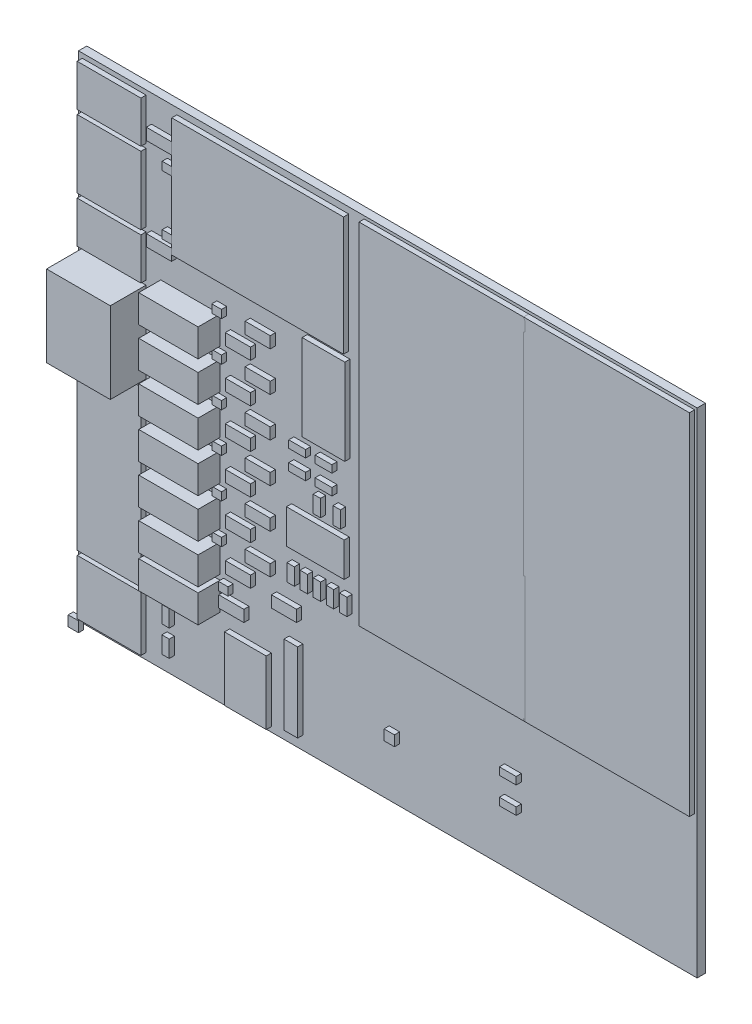
SolidWorks part; units mm, degrees
ref_plane "Front Plane" through (0, 0, 0) normal (0, 0, 1) x (1, 0, 0)
ref_plane "Top Plane" through (0, 0, 0) normal (0, 1, 0) x (1, 0, 0)
ref_plane "Right Plane" through (0, 0, 0) normal (1, 0, 0) x (0, 0, -1)
sketch "Sketch1" plane through (0, 0, 0) normal (0, 0, 1) x (1, 0, 0)
  line L0 (0, 0) -> (119.36, 0)
  line L1 (119.36, 0) -> (119.36, 95.25)
  line L2 (119.36, 95.25) -> (0, 95.25)
  line L3 (0, 95.25) -> (0, 0)
extrude "BOARD" add sketch "Sketch1" along normal blind 1.6 separate body
ref_plane "Plane1" through (0, 0, 1.6) normal (0, 0, 1) x (1, 0, 0)
sketch "Sketch2" plane through (0, 0, 1.6) normal (0, 0, 1) x (1, 0, 0)
  line L0 (42.6354, 30.8354) -> (42.6354, 27.5846)
  line L1 (42.6354, 27.5846) -> (41.21, 27.5846)
  line L2 (41.21, 27.5846) -> (41.21, 30.8354)
  line L3 (41.21, 30.8354) -> (42.6354, 30.8354)
extrude "0603-1" add sketch "Sketch2" along normal blind 1 separate body
sketch "Sketch3" plane through (0, 0, 1.6) normal (0, 0, 1) x (1, 0, 0)
  line L0 (47.7154, 30.8354) -> (47.7154, 27.5846)
  line L1 (47.7154, 27.5846) -> (46.29, 27.5846)
  line L2 (46.29, 27.5846) -> (46.29, 30.8354)
  line L3 (46.29, 30.8354) -> (47.7154, 30.8354)
extrude "0603-2" add sketch "Sketch3" along normal blind 1 separate body
sketch "Sketch4" plane through (0, 0, 1.6) normal (0, 0, 1) x (1, 0, 0)
  line L0 (45.1754, 30.8354) -> (45.1754, 27.5846)
  line L1 (45.1754, 27.5846) -> (43.75, 27.5846)
  line L2 (43.75, 27.5846) -> (43.75, 30.8354)
  line L3 (43.75, 30.8354) -> (45.1754, 30.8354)
extrude "0603-3" add sketch "Sketch4" along normal blind 1 separate body
sketch "Sketch5" plane through (0, 0, 1.6) normal (0, 0, 1) x (1, 0, 0)
  line L0 (48.8046, 27.5846) -> (48.8046, 30.8354)
  line L1 (48.8046, 30.8354) -> (50.23, 30.8354)
  line L2 (50.23, 30.8354) -> (50.23, 27.5846)
  line L3 (50.23, 27.5846) -> (48.8046, 27.5846)
extrude "0603-4" add sketch "Sketch5" along normal blind 1 separate body
sketch "Sketch6" plane through (0, 0, 1.6) normal (0, 0, 1) x (1, 0, 0)
  line L0 (44.1452, 53.3146) -> (44.1452, 69.9135)
  line L1 (44.1452, 69.9135) -> (52.3748, 69.9135)
  line L2 (52.3748, 69.9135) -> (52.3748, 53.3146)
  line L3 (52.3748, 53.3146) -> (44.1452, 53.3146)
extrude "TLN6-CUST-1" add sketch "Sketch6" along normal blind 1 separate body
sketch "Sketch7" plane through (0, 0, 1.6) normal (0, 0, 1) x (1, 0, 0)
  line L0 (28.575, 65.2559) -> (26.7084, 65.2559)
  line L1 (26.7084, 65.2559) -> (26.7084, 66.8241)
  line L2 (26.7084, 66.8241) -> (28.575, 66.8241)
  line L3 (28.575, 66.8241) -> (28.575, 65.2559)
extrude "LED-1206-1" add sketch "Sketch7" along normal blind 1 separate body
sketch "Sketch8" plane through (0, 0, 1.6) normal (0, 0, 1) x (1, 0, 0)
  line L0 (28.575, 57.6359) -> (26.7084, 57.6359)
  line L1 (26.7084, 57.6359) -> (26.7084, 59.2041)
  line L2 (26.7084, 59.2041) -> (28.575, 59.2041)
  line L3 (28.575, 59.2041) -> (28.575, 57.6359)
extrude "LED-1206-2" add sketch "Sketch8" along normal blind 1 separate body
sketch "Sketch9" plane through (0, 0, 1.6) normal (0, 0, 1) x (1, 0, 0)
  line L0 (28.575, 50.0159) -> (26.7084, 50.0159)
  line L1 (26.7084, 50.0159) -> (26.7084, 51.5841)
  line L2 (26.7084, 51.5841) -> (28.575, 51.5841)
  line L3 (28.575, 51.5841) -> (28.575, 50.0159)
extrude "LED-1206-3" add sketch "Sketch9" along normal blind 1 separate body
sketch "Sketch10" plane through (0, 0, 1.6) normal (0, 0, 1) x (1, 0, 0)
  line L0 (28.575, 42.3959) -> (26.7084, 42.3959)
  line L1 (26.7084, 42.3959) -> (26.7084, 43.9641)
  line L2 (26.7084, 43.9641) -> (28.575, 43.9641)
  line L3 (28.575, 43.9641) -> (28.575, 42.3959)
extrude "LED-1206-4" add sketch "Sketch10" along normal blind 1 separate body
sketch "Sketch11" plane through (0, 0, 1.6) normal (0, 0, 1) x (1, 0, 0)
  line L0 (28.575, 34.7759) -> (26.7084, 34.7759)
  line L1 (26.7084, 34.7759) -> (26.7084, 36.3441)
  line L2 (26.7084, 36.3441) -> (28.575, 36.3441)
  line L3 (28.575, 36.3441) -> (28.575, 34.7759)
extrude "LED-1206-5" add sketch "Sketch11" along normal blind 1 separate body
sketch "Sketch12" plane through (0, 0, 1.6) normal (0, 0, 1) x (1, 0, 0)
  line L0 (28.575, 27.1559) -> (26.7084, 27.1559)
  line L1 (26.7084, 27.1559) -> (26.7084, 28.7241)
  line L2 (26.7084, 28.7241) -> (28.575, 28.7241)
  line L3 (28.575, 28.7241) -> (28.575, 27.1559)
extrude "LED-1206-6" add sketch "Sketch12" along normal blind 1 separate body
sketch "Sketch13" plane through (0, 0, 1.6) normal (0, 0, 1) x (1, 0, 0)
  line L0 (29.845, 19.5359) -> (27.9784, 19.5359)
  line L1 (27.9784, 19.5359) -> (27.9784, 21.1041)
  line L2 (27.9784, 21.1041) -> (29.845, 21.1041)
  line L3 (29.845, 21.1041) -> (29.845, 19.5359)
extrude "LED-1206-7" add sketch "Sketch13" along normal blind 1 separate body
sketch "Sketch14" plane through (0, 0, 1.6) normal (0, 0, 1) x (1, 0, 0)
  line L0 (18.9865, 94.0435) -> (52.1335, 94.0435)
  line L1 (52.1335, 94.0435) -> (52.1335, 71.12)
  line L2 (52.1335, 71.12) -> (18.9865, 71.12)
  line L3 (18.9865, 71.12) -> (18.9865, 94.0435)
extrude "KHHD006A0A-1" add sketch "Sketch14" along normal blind 1 separate body
sketch "Sketch15" plane through (0, 0, 1.6) normal (0, 0, 1) x (1, 0, 0)
  line L0 (1, -1) -> (-1, -1)
  line L1 (-1, -1) -> (-1, 1)
  line L2 (-1, 1) -> (1, 1)
  line L3 (1, 1) -> (1, -1)
extrude "CREATIVE_COMMONS-1" add sketch "Sketch15" along normal blind 1 separate body
sketch "Sketch16" plane through (0, 0, 1.6) normal (0, 0, 1) x (1, 0, 0)
  line L0 (55.12, 27.215) -> (55.12, 94.705)
  line L1 (55.12, 94.705) -> (87.12, 94.705)
  line L2 (87.12, 94.705) -> (87.12, 27.215)
  line L3 (87.12, 27.215) -> (55.12, 27.215)
extrude "RASPBERRYPIZEROWV13-1" add sketch "Sketch16" along normal blind 1 separate body
sketch "Sketch17" plane through (0, 0, 1.6) normal (0, 0, 1) x (1, 0, 0)
  line L0 (86.87, 27.215) -> (86.87, 94.705)
  line L1 (86.87, 94.705) -> (118.87, 94.705)
  line L2 (118.87, 94.705) -> (118.87, 27.215)
  line L3 (118.87, 27.215) -> (86.87, 27.215)
extrude "RASPBERRYPIZEROWV13-2" add sketch "Sketch17" along normal blind 1 separate body
sketch "Sketch18" plane through (0, 0, 1.6) normal (0, 0, 1) x (1, 0, 0)
  line L0 (61.96, 12.43) -> (61.96, 10.43)
  line L1 (61.96, 10.43) -> (59.96, 10.43)
  line L2 (59.96, 10.43) -> (59.96, 12.43)
  line L3 (59.96, 12.43) -> (61.96, 12.43)
extrude "PRO-MINI-2-1" add sketch "Sketch18" along normal blind 1 separate body
sketch "Sketch19" plane through (0, 0, 1.6) normal (0, 0, 1) x (1, 0, 0)
  line L0 (41.1163, 40.132) -> (52.2516, 40.132)
  line L1 (52.2516, 40.132) -> (52.2516, 33.528)
  line L2 (52.2516, 33.528) -> (41.1163, 33.528)
  line L3 (41.1163, 33.528) -> (41.1163, 40.132)
extrude "SO16-1" add sketch "Sketch19" along normal blind 1 separate body
sketch "Sketch20" plane through (0, 0, 1.6) normal (0, 0, 1) x (1, 0, 0)
  line L0 (13.035, 85.475) -> (13.035, 72.34)
  line L1 (13.035, 72.34) -> (0.735, 72.34)
  line L2 (0.735, 72.34) -> (0.735, 85.475)
  line L3 (0.735, 85.475) -> (13.035, 85.475)
extrude "4PIN-1" add sketch "Sketch20" along normal blind 1 separate body
sketch "Sketch21" plane through (0, 0, 1.6) normal (0, 0, 1) x (1, 0, 0)
  line L0 (43.2816, 17.78) -> (43.2816, 2.54)
  line L1 (43.2816, 2.54) -> (40.64, 2.54)
  line L2 (40.64, 2.54) -> (40.64, 17.78)
  line L3 (40.64, 17.78) -> (43.2816, 17.78)
extrude "FTDI_BASIC-1" add sketch "Sketch21" along normal blind 1 separate body
sketch "Sketch22" plane through (0, 0, 1.6) normal (0, 0, 1) x (1, 0, 0)
  line L0 (13.035, 71.505) -> (13.035, 63.45)
  line L1 (13.035, 63.45) -> (0.735, 63.45)
  line L2 (0.735, 63.45) -> (0.735, 71.505)
  line L3 (0.735, 71.505) -> (13.035, 71.505)
extrude "2PIN-1" add sketch "Sketch22" along normal blind 1 separate body
sketch "Sketch23" plane through (0, 0, 1.6) normal (0, 0, 1) x (1, 0, 0)
  line L0 (13.035, 11.815) -> (13.035, 1.22)
  line L1 (13.035, 1.22) -> (0.735, 1.22)
  line L2 (0.735, 1.22) -> (0.735, 11.815)
  line L3 (0.735, 11.815) -> (13.035, 11.815)
extrude "3PIN-1" add sketch "Sketch23" along normal blind 1 separate body
sketch "Sketch24" plane through (0, 0, 1.6) normal (0, 0, 1) x (1, 0, 0)
  line L0 (13.035, 94.365) -> (13.035, 86.31)
  line L1 (13.035, 86.31) -> (0.735, 86.31)
  line L2 (0.735, 86.31) -> (0.735, 94.365)
  line L3 (0.735, 94.365) -> (13.035, 94.365)
extrude "2PIN-2" add sketch "Sketch24" along normal blind 1 separate body
sketch "Sketch25" plane through (0, 0, 1.6) normal (0, 0, 1) x (1, 0, 0)
  line L0 (13.035, 62.615) -> (13.035, 46.94)
  line L1 (13.035, 46.94) -> (0.735, 46.94)
  line L2 (0.735, 46.94) -> (0.735, 62.615)
  line L3 (0.735, 62.615) -> (13.035, 62.615)
extrude "SHDR5W90P0X250_1X5_1490X1150X6_6.900000-1" add sketch "Sketch25" along normal blind 6.9 separate body
sketch "Sketch26" plane through (0, 0, 1.6) normal (0, 0, 1) x (1, 0, 0)
  line L0 (13.035, 46.105) -> (13.035, 12.65)
  line L1 (13.035, 12.65) -> (0.735, 12.65)
  line L2 (0.735, 12.65) -> (0.735, 46.105)
  line L3 (0.735, 46.105) -> (13.035, 46.105)
extrude "12PIN-1" add sketch "Sketch26" along normal blind 1 separate body
sketch "Sketch27" plane through (0, 0, 1.6) normal (0, 0, 1) x (1, 0, 0)
  line L0 (37.215, 0.935) -> (29.16, 0.935)
  line L1 (29.16, 0.935) -> (29.16, 13.235)
  line L2 (29.16, 13.235) -> (37.215, 13.235)
  line L3 (37.215, 13.235) -> (37.215, 0.935)
extrude "2PIN-3" add sketch "Sketch27" along normal blind 1 separate body
sketch "Sketch28" plane through (0, 0, 1.6) normal (0, 0, 1) x (1, 0, 0)
  line L0 (41.5546, 51.5254) -> (44.8054, 51.5254)
  line L1 (44.8054, 51.5254) -> (44.8054, 50.1)
  line L2 (44.8054, 50.1) -> (41.5546, 50.1)
  line L3 (41.5546, 50.1) -> (41.5546, 51.5254)
extrude "0603-5" add sketch "Sketch28" along normal blind 1 separate body
sketch "Sketch29" plane through (0, 0, 1.6) normal (0, 0, 1) x (1, 0, 0)
  line L0 (46.6346, 51.5254) -> (49.8854, 51.5254)
  line L1 (49.8854, 51.5254) -> (49.8854, 50.1)
  line L2 (49.8854, 50.1) -> (46.6346, 50.1)
  line L3 (46.6346, 50.1) -> (46.6346, 51.5254)
extrude "0603-6" add sketch "Sketch29" along normal blind 1 separate body
sketch "Sketch30" plane through (0, 0, 1.6) normal (0, 0, 1) x (1, 0, 0)
  line L0 (46.2646, 41.5546) -> (46.2646, 44.8054)
  line L1 (46.2646, 44.8054) -> (47.69, 44.8054)
  line L2 (47.69, 44.8054) -> (47.69, 41.5546)
  line L3 (47.69, 41.5546) -> (46.2646, 41.5546)
extrude "0603-7" add sketch "Sketch30" along normal blind 1 separate body
sketch "Sketch31" plane through (0, 0, 1.6) normal (0, 0, 1) x (1, 0, 0)
  line L0 (52.7954, 30.8354) -> (52.7954, 27.5846)
  line L1 (52.7954, 27.5846) -> (51.37, 27.5846)
  line L2 (51.37, 27.5846) -> (51.37, 30.8354)
  line L3 (51.37, 30.8354) -> (52.7954, 30.8354)
extrude "0603-8" add sketch "Sketch31" along normal blind 1 separate body
sketch "Sketch32" plane through (0, 0, 1.6) normal (0, 0, 1) x (1, 0, 0)
  line L0 (51.5254, 44.8054) -> (51.5254, 41.5546)
  line L1 (51.5254, 41.5546) -> (50.1, 41.5546)
  line L2 (50.1, 41.5546) -> (50.1, 44.8054)
  line L3 (50.1, 44.8054) -> (51.5254, 44.8054)
extrude "0603-9" add sketch "Sketch32" along normal blind 1 separate body
sketch "Sketch33" plane through (0, 0, 1.6) normal (0, 0, 1) x (1, 0, 0)
  line L0 (18.5054, 6.7054) -> (18.5054, 3.4546)
  line L1 (18.5054, 3.4546) -> (17.08, 3.4546)
  line L2 (17.08, 3.4546) -> (17.08, 6.7054)
  line L3 (17.08, 6.7054) -> (18.5054, 6.7054)
extrude "0603-10" add sketch "Sketch33" along normal blind 1 separate body
sketch "Sketch34" plane through (0, 0, 1.6) normal (0, 0, 1) x (1, 0, 0)
  line L0 (18.5054, 11.7854) -> (18.5054, 8.5346)
  line L1 (18.5054, 8.5346) -> (17.08, 8.5346)
  line L2 (17.08, 8.5346) -> (17.08, 11.7854)
  line L3 (17.08, 11.7854) -> (18.5054, 11.7854)
extrude "0603-11" add sketch "Sketch34" along normal blind 1 separate body
sketch "Sketch35" plane through (0, 0, 1.6) normal (0, 0, 1) x (1, 0, 0)
  line L0 (41.5546, 47.7154) -> (44.8054, 47.7154)
  line L1 (44.8054, 47.7154) -> (44.8054, 46.29)
  line L2 (44.8054, 46.29) -> (41.5546, 46.29)
  line L3 (41.5546, 46.29) -> (41.5546, 47.7154)
extrude "0603-12" add sketch "Sketch35" along normal blind 1 separate body
sketch "Sketch36" plane through (0, 0, 1.6) normal (0, 0, 1) x (1, 0, 0)
  line L0 (46.6346, 47.7154) -> (49.8854, 47.7154)
  line L1 (49.8854, 47.7154) -> (49.8854, 46.29)
  line L2 (49.8854, 46.29) -> (46.6346, 46.29)
  line L3 (46.6346, 46.29) -> (46.6346, 47.7154)
extrude "0603-13" add sketch "Sketch36" along normal blind 1 separate body
sketch "Sketch37" plane through (0, 0, 1.6) normal (0, 0, 1) x (1, 0, 0)
  line L0 (34.1754, 23.0046) -> (29.3246, 23.0046)
  line L1 (29.3246, 23.0046) -> (29.3246, 25.23)
  line L2 (29.3246, 25.23) -> (34.1754, 25.23)
  line L3 (34.1754, 25.23) -> (34.1754, 23.0046)
extrude "1206-1" add sketch "Sketch37" along normal blind 1 separate body
sketch "Sketch38" plane through (0, 0, 1.6) normal (0, 0, 1) x (1, 0, 0)
  line L0 (37.9854, 26.8146) -> (33.1346, 26.8146)
  line L1 (33.1346, 26.8146) -> (33.1346, 29.04)
  line L2 (33.1346, 29.04) -> (37.9854, 29.04)
  line L3 (37.9854, 29.04) -> (37.9854, 26.8146)
extrude "1206-2" add sketch "Sketch38" along normal blind 1 separate body
sketch "Sketch39" plane through (0, 0, 1.6) normal (0, 0, 1) x (1, 0, 0)
  line L0 (34.1754, 30.6246) -> (29.3246, 30.6246)
  line L1 (29.3246, 30.6246) -> (29.3246, 32.85)
  line L2 (29.3246, 32.85) -> (34.1754, 32.85)
  line L3 (34.1754, 32.85) -> (34.1754, 30.6246)
extrude "1206-3" add sketch "Sketch39" along normal blind 1 separate body
sketch "Sketch40" plane through (0, 0, 1.6) normal (0, 0, 1) x (1, 0, 0)
  line L0 (37.9854, 34.4346) -> (33.1346, 34.4346)
  line L1 (33.1346, 34.4346) -> (33.1346, 36.66)
  line L2 (33.1346, 36.66) -> (37.9854, 36.66)
  line L3 (37.9854, 36.66) -> (37.9854, 34.4346)
extrude "1206-4" add sketch "Sketch40" along normal blind 1 separate body
sketch "Sketch41" plane through (0, 0, 1.6) normal (0, 0, 1) x (1, 0, 0)
  line L0 (34.1754, 38.2446) -> (29.3246, 38.2446)
  line L1 (29.3246, 38.2446) -> (29.3246, 40.47)
  line L2 (29.3246, 40.47) -> (34.1754, 40.47)
  line L3 (34.1754, 40.47) -> (34.1754, 38.2446)
extrude "1206-5" add sketch "Sketch41" along normal blind 1 separate body
sketch "Sketch42" plane through (0, 0, 1.6) normal (0, 0, 1) x (1, 0, 0)
  line L0 (37.9854, 42.0546) -> (33.1346, 42.0546)
  line L1 (33.1346, 42.0546) -> (33.1346, 44.28)
  line L2 (33.1346, 44.28) -> (37.9854, 44.28)
  line L3 (37.9854, 44.28) -> (37.9854, 42.0546)
extrude "1206-6" add sketch "Sketch42" along normal blind 1 separate body
sketch "Sketch43" plane through (0, 0, 1.6) normal (0, 0, 1) x (1, 0, 0)
  line L0 (34.1754, 45.8646) -> (29.3246, 45.8646)
  line L1 (29.3246, 45.8646) -> (29.3246, 48.09)
  line L2 (29.3246, 48.09) -> (34.1754, 48.09)
  line L3 (34.1754, 48.09) -> (34.1754, 45.8646)
extrude "1206-7" add sketch "Sketch43" along normal blind 1 separate body
sketch "Sketch44" plane through (0, 0, 1.6) normal (0, 0, 1) x (1, 0, 0)
  line L0 (37.9854, 49.6746) -> (33.1346, 49.6746)
  line L1 (33.1346, 49.6746) -> (33.1346, 51.9)
  line L2 (33.1346, 51.9) -> (37.9854, 51.9)
  line L3 (37.9854, 51.9) -> (37.9854, 49.6746)
extrude "1206-8" add sketch "Sketch44" along normal blind 1 separate body
sketch "Sketch45" plane through (0, 0, 1.6) normal (0, 0, 1) x (1, 0, 0)
  line L0 (34.1754, 53.4846) -> (29.3246, 53.4846)
  line L1 (29.3246, 53.4846) -> (29.3246, 55.71)
  line L2 (29.3246, 55.71) -> (34.1754, 55.71)
  line L3 (34.1754, 55.71) -> (34.1754, 53.4846)
extrude "1206-9" add sketch "Sketch45" along normal blind 1 separate body
sketch "Sketch46" plane through (0, 0, 1.6) normal (0, 0, 1) x (1, 0, 0)
  line L0 (37.9854, 57.2946) -> (33.1346, 57.2946)
  line L1 (33.1346, 57.2946) -> (33.1346, 59.52)
  line L2 (33.1346, 59.52) -> (37.9854, 59.52)
  line L3 (37.9854, 59.52) -> (37.9854, 57.2946)
extrude "1206-10" add sketch "Sketch46" along normal blind 1 separate body
sketch "Sketch47" plane through (0, 0, 1.6) normal (0, 0, 1) x (1, 0, 0)
  line L0 (34.1754, 61.1046) -> (29.3246, 61.1046)
  line L1 (29.3246, 61.1046) -> (29.3246, 63.33)
  line L2 (29.3246, 63.33) -> (34.1754, 63.33)
  line L3 (34.1754, 63.33) -> (34.1754, 61.1046)
extrude "1206-11" add sketch "Sketch47" along normal blind 1 separate body
sketch "Sketch48" plane through (0, 0, 1.6) normal (0, 0, 1) x (1, 0, 0)
  line L0 (37.9854, 64.9146) -> (33.1346, 64.9146)
  line L1 (33.1346, 64.9146) -> (33.1346, 67.14)
  line L2 (33.1346, 67.14) -> (37.9854, 67.14)
  line L3 (37.9854, 67.14) -> (37.9854, 64.9146)
extrude "1206-12" add sketch "Sketch48" along normal blind 1 separate body
sketch "Sketch49" plane through (0, 0, 1.6) normal (0, 0, 1) x (1, 0, 0)
  line L0 (14.0846, 90.0254) -> (18.9354, 90.0254)
  line L1 (18.9354, 90.0254) -> (18.9354, 87.8)
  line L2 (18.9354, 87.8) -> (14.0846, 87.8)
  line L3 (14.0846, 87.8) -> (14.0846, 90.0254)
extrude "1206-13" add sketch "Sketch49" along normal blind 1 separate body
sketch "Sketch50" plane through (0, 0, 1.6) normal (0, 0, 1) x (1, 0, 0)
  line L0 (14.0846, 72.2454) -> (18.9354, 72.2454)
  line L1 (18.9354, 72.2454) -> (18.9354, 70.02)
  line L2 (18.9354, 70.02) -> (14.0846, 70.02)
  line L3 (14.0846, 70.02) -> (14.0846, 72.2454)
extrude "1206-14" add sketch "Sketch50" along normal blind 1 separate body
sketch "Sketch51" plane through (0, 0, 1.6) normal (0, 0, 1) x (1, 0, 0)
  line L0 (43.0654, 21.7346) -> (38.2146, 21.7346)
  line L1 (38.2146, 21.7346) -> (38.2146, 23.96)
  line L2 (38.2146, 23.96) -> (43.0654, 23.96)
  line L3 (43.0654, 23.96) -> (43.0654, 21.7346)
extrude "1206-15" add sketch "Sketch51" along normal blind 1 separate body
sketch "Sketch52" plane through (0, 0, 1.6) normal (0, 0, 1) x (1, 0, 0)
  line L0 (32.9054, 16.6546) -> (28.0546, 16.6546)
  line L1 (28.0546, 16.6546) -> (28.0546, 18.88)
  line L2 (28.0546, 18.88) -> (32.9054, 18.88)
  line L3 (32.9054, 18.88) -> (32.9054, 16.6546)
extrude "1206-16" add sketch "Sketch52" along normal blind 1 separate body
sketch "Sketch53" plane through (0, 0, 1.6) normal (0, 0, 1) x (1, 0, 0)
  line L0 (85.4454, 10.7046) -> (82.1946, 10.7046)
  line L1 (82.1946, 10.7046) -> (82.1946, 12.13)
  line L2 (82.1946, 12.13) -> (85.4454, 12.13)
  line L3 (85.4454, 12.13) -> (85.4454, 10.7046)
extrude "0603-14" add sketch "Sketch53" along normal blind 1 separate body
sketch "Sketch54" plane through (0, 0, 1.6) normal (0, 0, 1) x (1, 0, 0)
  line L0 (85.4454, 15.7846) -> (82.1946, 15.7846)
  line L1 (82.1946, 15.7846) -> (82.1946, 17.21)
  line L2 (82.1946, 17.21) -> (85.4454, 17.21)
  line L3 (85.4454, 17.21) -> (85.4454, 15.7846)
extrude "0603-15" add sketch "Sketch54" along normal blind 1 separate body
sketch "Sketch55" plane through (0, 0, 1.6) normal (0, 0, 1) x (1, 0, 0)
  line L0 (27.315, 59.54) -> (15.865, 59.54)
  line L1 (15.865, 59.54) -> (15.865, 64.895)
  line L2 (15.865, 64.895) -> (27.315, 64.895)
  line L3 (27.315, 64.895) -> (27.315, 59.54)
extrude "SOP254P1000X425-4N_4.250000-1" add sketch "Sketch55" along normal blind 4.25 separate body
sketch "Sketch56" plane through (0, 0, 1.6) normal (0, 0, 1) x (1, 0, 0)
  line L0 (27.315, 51.92) -> (15.865, 51.92)
  line L1 (15.865, 51.92) -> (15.865, 57.275)
  line L2 (15.865, 57.275) -> (27.315, 57.275)
  line L3 (27.315, 57.275) -> (27.315, 51.92)
extrude "SOP254P1000X425-4N_4.250000-2" add sketch "Sketch56" along normal blind 4.25 separate body
sketch "Sketch57" plane through (0, 0, 1.6) normal (0, 0, 1) x (1, 0, 0)
  line L0 (27.315, 44.3) -> (15.865, 44.3)
  line L1 (15.865, 44.3) -> (15.865, 49.655)
  line L2 (15.865, 49.655) -> (27.315, 49.655)
  line L3 (27.315, 49.655) -> (27.315, 44.3)
extrude "SOP254P1000X425-4N_4.250000-3" add sketch "Sketch57" along normal blind 4.25 separate body
sketch "Sketch58" plane through (0, 0, 1.6) normal (0, 0, 1) x (1, 0, 0)
  line L0 (27.315, 36.68) -> (15.865, 36.68)
  line L1 (15.865, 36.68) -> (15.865, 42.035)
  line L2 (15.865, 42.035) -> (27.315, 42.035)
  line L3 (27.315, 42.035) -> (27.315, 36.68)
extrude "SOP254P1000X425-4N_4.250000-4" add sketch "Sketch58" along normal blind 4.25 separate body
sketch "Sketch59" plane through (0, 0, 1.6) normal (0, 0, 1) x (1, 0, 0)
  line L0 (27.315, 29.06) -> (15.865, 29.06)
  line L1 (15.865, 29.06) -> (15.865, 34.415)
  line L2 (15.865, 34.415) -> (27.315, 34.415)
  line L3 (27.315, 34.415) -> (27.315, 29.06)
extrude "SOP254P1000X425-4N_4.250000-5" add sketch "Sketch59" along normal blind 4.25 separate body
sketch "Sketch60" plane through (0, 0, 1.6) normal (0, 0, 1) x (1, 0, 0)
  line L0 (27.315, 21.44) -> (15.865, 21.44)
  line L1 (15.865, 21.44) -> (15.865, 26.795)
  line L2 (15.865, 26.795) -> (27.315, 26.795)
  line L3 (27.315, 26.795) -> (27.315, 21.44)
extrude "SOP254P1000X425-4N_4.250000-6" add sketch "Sketch60" along normal blind 4.25 separate body
sketch "Sketch61" plane through (0, 0, 1.6) normal (0, 0, 1) x (1, 0, 0)
  line L0 (27.315, 15.09) -> (15.865, 15.09)
  line L1 (15.865, 15.09) -> (15.865, 20.445)
  line L2 (15.865, 20.445) -> (27.315, 20.445)
  line L3 (27.315, 20.445) -> (27.315, 15.09)
extrude "SOP254P1000X425-4N_4.250000-7" add sketch "Sketch61" along normal blind 4.25 separate body
sketch "Sketch62" plane through (0, 0, 1.6) normal (0, 0, 1) x (1, 0, 0)
  line L0 (17.145, 74.4441) -> (19.0116, 74.4441)
  line L1 (19.0116, 74.4441) -> (19.0116, 72.8759)
  line L2 (19.0116, 72.8759) -> (17.145, 72.8759)
  line L3 (17.145, 72.8759) -> (17.145, 74.4441)
extrude "LED-1206-8" add sketch "Sketch62" along normal blind 1 separate body
sketch "Sketch63" plane through (0, 0, 1.6) normal (0, 0, 1) x (1, 0, 0)
  line L0 (17.145, 85.8741) -> (19.0116, 85.8741)
  line L1 (19.0116, 85.8741) -> (19.0116, 84.3059)
  line L2 (19.0116, 84.3059) -> (17.145, 84.3059)
  line L3 (17.145, 84.3059) -> (17.145, 85.8741)
extrude "LED-1206-9" add sketch "Sketch63" along normal blind 1 separate body
